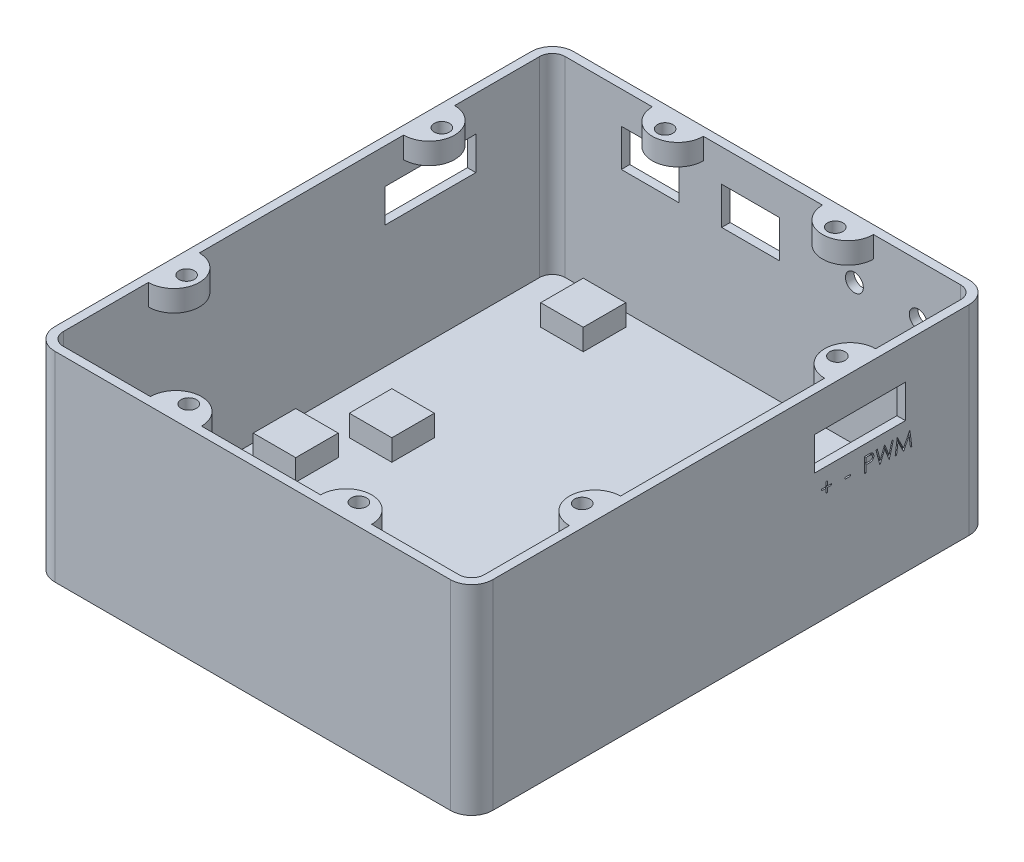
SolidWorks part; units mm, degrees
ref_plane "Alzado" through (0, 0, 0) normal (0, 0, 1) x (1, 0, 0)
ref_plane "Planta" through (0, 0, 0) normal (0, 1, 0) x (1, 0, 0)
ref_plane "Vista lateral" through (0, 0, 0) normal (1, 0, 0) x (0, 0, -1)
sketch "Croquis1" plane through (0, 0, 0) normal (0, 1, 0) x (1, 0, 0)
  line L0 (0, 0) -> (-10, 0) construction
  line L1 (0, 0) -> (93, 0) construction
  line L2 (0, 0) -> (0, 112) construction
  line L3 (0, 112) -> (93, 112) construction
  line L4 (93, 0) -> (93, 112) construction
  line L5 (0, 0) -> (0, -10) construction
  line L6 (0, -10) -> (-10, -10) construction
  line L7 (-10, -10) -> (-10, 0) construction
  line L8 (0, 0) -> (-3.5355, -3.5355) construction
  line L9 (-10, 0) -> (0, -10) construction
  line L10 (-5, -5) -> (-10, -10) construction
  line L15 (0, -5) -> (93, -5)
  line L16 (-5, 0) -> (-5, 112)
  line L17 (0, 117) -> (93, 117)
  line L18 (98, 0) -> (98, 112)
  arc A0 (-5, 0) -> (0, -5) centre (0, 0) ccw
  arc A1 (93, -5) -> (98, 0) centre (93, 0) ccw
  arc A2 (98, 112) -> (93, 117) centre (93, 112) ccw
  arc A3 (0, 117) -> (-5, 112) centre (0, 112) ccw
  point P10 (-5, -5)
  dimension "D5" = 5
  dimension "D1" = 112
  dimension "D2" = 93
extrude "Saliente-Extruir2" add sketch "Croquis1" along normal blind 47
shell "Vaciado3" thickness 2
sketch "Croquis2" plane through (0, 2, 0) normal (0, 1, 0) x (1, 0, 0)
  line L0 (46.5, -3) -> (46.5, 115) construction
  line L1 (0, -3) -> (93, -3) construction
  line L2 (93, 115) -> (0, 115) construction
  line L3 (96, 56) -> (-3, 56) construction
  line L4 (96, 0) -> (96, 112) construction
  line L5 (-3, 112) -> (-3, 0) construction
  line L6 (46.5, -3) -> (46.5, 0) construction
  line L7 (46.5, 115) -> (46.5, 112) construction
  line L8 (46.5, 0) -> (46.5, 51) construction
  line L9 (46.5, 115) -> (46.5, 60) construction
  line L10 (46.5, 112) -> (46.5, 57) construction
  line L11 (46.5, 112) -> (7.25, 112) construction
  line L12 (46.5, 112) -> (85.75, 112) construction
  line L13 (46.5, 0) -> (0, 0) construction
  line L14 (7.25, 57) -> (85.75, 57) construction
  line L15 (7.25, 57) -> (7.25, 112) construction
  line L16 (7.25, 112) -> (85.75, 112) construction
  line L17 (85.75, 57) -> (85.75, 112) construction
  line L18 (46.5, 0) -> (93, 0) construction
  line L20 (0, 0) -> (93, 0) construction
  line L21 (0, 0) -> (0, 51.6536) construction
  line L22 (0, 51.6536) -> (93, 51.6536) construction
  line L23 (93, 0) -> (93, 51.6536) construction
  line L24 (0, 0) -> (10, 0)
  line L25 (0, 0) -> (0, 10)
  line L26 (0, 10) -> (10, 10)
  line L27 (10, 0) -> (10, 10)
  line L28 (93, 0) -> (83, 0)
  line L29 (93, 0) -> (93, 10)
  line L30 (93, 10) -> (83, 10)
  line L31 (83, 0) -> (83, 10)
  line L32 (0, 51.6536) -> (10, 51.6536)
  line L33 (0, 51.6536) -> (0, 41.6536)
  line L34 (0, 41.6536) -> (10, 41.6536)
  line L35 (10, 51.6536) -> (10, 41.6536)
  line L36 (93, 51.6536) -> (83, 51.6536)
  line L37 (93, 51.6536) -> (93, 41.6536)
  line L38 (93, 41.6536) -> (83, 41.6536)
  line L39 (83, 51.6536) -> (83, 41.6536)
  line L40 (7.25, 57) -> (17.25, 57)
  line L41 (7.25, 57) -> (7.25, 67)
  line L42 (7.25, 67) -> (17.25, 67)
  line L43 (17.25, 57) -> (17.25, 67)
  line L44 (7.25, 112) -> (17.25, 112)
  line L45 (7.25, 112) -> (7.25, 102)
  line L46 (7.25, 102) -> (17.25, 102)
  line L47 (17.25, 112) -> (17.25, 102)
  line L48 (85.75, 57) -> (75.75, 57)
  line L49 (85.75, 57) -> (85.75, 67)
  line L50 (85.75, 67) -> (75.75, 67)
  line L51 (75.75, 57) -> (75.75, 67)
  line L52 (85.75, 112) -> (75.75, 112)
  line L53 (85.75, 112) -> (85.75, 102)
  line L54 (85.75, 102) -> (75.75, 102)
  line L55 (75.75, 112) -> (75.75, 102)
  dimension "D1" = 3
  dimension "D2" = 3
  dimension "D3" = 51
  dimension "D4" = 55
  dimension "D5" = 39.25
  dimension "D6" = 39.25
  dimension "D7" = 46.5
  dimension "D8" = 46.5
  dimension "D9" = 10
  dimension "D10" = 10
  dimension "D11" = 10
  dimension "D12" = 10
  dimension "D13" = 10
  dimension "D14" = 10
  dimension "D15" = 10
  dimension "D16" = 10
  dimension "D17" = 10
  dimension "D18" = 10
  dimension "D19" = 10
  dimension "D20" = 10
  dimension "D21" = 10
extrude "Saliente-Extruir3" add sketch "Croquis2" along normal blind 5
sketch "Croquis3" plane through (0, 47, 0) normal (0, 1, 0) x (1, 0, 0)
  line L0 (46.5, -3) -> (66.5, -3) construction
  line L1 (0, -3) -> (93, -3) construction
  line L2 (0, -3) -> (93, -3) construction
  line L3 (46.5, -3) -> (26.5, -3) construction
  line L4 (-3, 56) -> (-3, 86) construction
  line L5 (-3, 112) -> (-3, 0) construction
  line L6 (-3, 56) -> (-3, 26) construction
  line L7 (-3, 112) -> (-3, 0) construction
  line L8 (96, 56) -> (96, 86) construction
  line L9 (96, 0) -> (96, 112) construction
  line L10 (96, 56) -> (96, 26) construction
  line L11 (96, 0) -> (96, 112) construction
  line L12 (46.5, 115) -> (26.5, 115) construction
  line L13 (93, 115) -> (0, 115) construction
  line L14 (46.5, 115) -> (66.5, 115) construction
  line L15 (93, 115) -> (0, 115) construction
  line L16 (-3, 86) -> (3, 86) construction
  line L17 (-3, 26) -> (3, 26) construction
  line L18 (26.5, -3) -> (26.5, 3) construction
  line L19 (66.5, -3) -> (66.5, 3) construction
  line L20 (96, 26) -> (90, 26) construction
  line L21 (96, 86) -> (90, 86) construction
  line L22 (26.5, 115) -> (26.5, 109) construction
  line L23 (66.5, 115) -> (66.5, 109) construction
  line L24 (-3, 92) -> (-3, 80)
  line L25 (-3, 32) -> (-3, 20)
  line L26 (32.5, -3) -> (20.5, -3)
  line L27 (72.5, -3) -> (60.5, -3)
  line L28 (96, 32) -> (96, 20)
  line L29 (96, 92) -> (96, 80)
  line L30 (20.5, 115) -> (32.5, 115)
  line L31 (60.5, 115) -> (72.5, 115)
  circle A0 centre (-3, 86) radius 6 construction
  circle A1 centre (-3, 26) radius 6 construction
  circle A2 centre (96, 86) radius 6 construction
  circle A3 centre (96, 26) radius 6 construction
  circle A4 centre (26.5, 115) radius 6 construction
  circle A5 centre (66.5, 115) radius 6 construction
  circle A6 centre (26.5, -3) radius 6 construction
  circle A7 centre (66.5, -3) radius 6 construction
  arc A8 (20.5, 115) -> (32.5, 115) centre (26.5, 115) ccw
  arc A9 (72.5, 115) -> (60.5, 115) centre (66.5, 115) cw
  arc A10 (-3, 80) -> (-3, 92) centre (-3, 86) ccw
  arc A11 (-3, 20) -> (-3, 32) centre (-3, 26) ccw
  arc A12 (32.5, -3) -> (20.5, -3) centre (26.5, -3) ccw
  arc A13 (72.5, -3) -> (60.5, -3) centre (66.5, -3) ccw
  arc A14 (96, 32) -> (96, 20) centre (96, 26) ccw
  arc A15 (96, 92) -> (96, 80) centre (96, 86) ccw
  circle A16 centre (0, 86) radius 1.8
  circle A17 centre (26.5, 112) radius 1.8
  circle A18 centre (66.5, 112) radius 1.8
  circle A19 centre (93, 86) radius 1.8
  circle A20 centre (93, 26) radius 1.8
  circle A21 centre (66.5, 0) radius 1.8
  circle A22 centre (26.5, 0) radius 1.8
  circle A23 centre (0, 26) radius 1.8
  dimension "D9" = 12
  dimension "D10" = 12
  dimension "D11" = 12
  dimension "D12" = 12
  dimension "D13" = 12
  dimension "D14" = 12
  dimension "D15" = 12
  dimension "D16" = 12
  dimension "D17" = 3.6
  dimension "D18" = 3.6
  dimension "D19" = 3.6
  dimension "D20" = 3.6
  dimension "D21" = 3.6
  dimension "D22" = 3.6
  dimension "D23" = 3.6
  dimension "D24" = 3.6
  dimension "D1" = 20
  dimension "D2" = 20
  dimension "D3" = 20
  dimension "D4" = 20
  dimension "D5" = 30
  dimension "D6" = 30
  dimension "D7" = 30
  dimension "D8" = 30
extrude "Saliente-Extruir4" add sketch "Croquis3" against normal blind 5
sketch "Croquis4" plane through (-5, 0, 0) normal (-1, 0, 0) x (0, 0, 1)
  line L0 (-112, 47) -> (-112, 0) construction
  line L1 (-112, 47) -> (-112, 38.7) construction
  line L2 (-112, 38.7) -> (-97, 38.7) construction
  line L4 (-97, 38.7) -> (-75.66, 38.7)
  line L5 (-97, 38.7) -> (-97, 30.86)
  line L6 (-97, 30.86) -> (-75.66, 30.86)
  line L7 (-75.66, 38.7) -> (-75.66, 30.86)
  dimension "D1" = 8.3
  dimension "D2" = 15
  dimension "D3" = 21.34
  dimension "D4" = 7.84
extrude "Cortar-Extruir1" cut sketch "Croquis4" against normal blind 120
sketch "Croquis5" plane through (0, 0, -117) normal (0, 0, -1) x (-1, 0, 0)
  line L0 (-93, 47) -> (-93, 35) construction
  line L1 (-93, 47) -> (-93, 0) construction
  line L2 (-93, 35) -> (-83, 35) construction
  line L3 (0, 47) -> (0, 35) construction
  line L4 (0, 47) -> (0, 0) construction
  line L5 (0, 35) -> (-20, 35) construction
  line L6 (-20, 35) -> (-13.2, 35) construction
  line L7 (-13.2, 35) -> (-13.2, 39.4) construction
  line L9 (-13.2, 39.4) -> (-26.8, 39.4)
  line L10 (-13.2, 39.4) -> (-13.2, 30.6)
  line L11 (-13.2, 30.6) -> (-26.8, 30.6)
  line L12 (-26.8, 39.4) -> (-26.8, 30.6)
  circle A0 centre (-83, 35) radius 2.1
  dimension "D3" = 4.2
  dimension "D1" = 12
  dimension "D2" = 10
  dimension "D4" = 12
  dimension "D5" = 20
  dimension "D6" = 6.8
  dimension "D7" = 4.4
  dimension "D8" = 13.6
  dimension "D9" = 8.8
extrude "Cortar-Extruir2" cut sketch "Croquis5" against normal blind 2
sketch "Croquis6" plane through (-5, 0, 0) normal (-1, 0, 0) x (0, 0, 1)
  line L0 (-86.33, 30.86) -> (-86.33, 24.86) construction
  line L1 (-97, 30.86) -> (-75.66, 30.86) construction
  line L2 (-86.33, 24.86) -> (-75.66, 24.86) construction
  line L3 (-75.66, 24.86) -> (-97, 24.86) construction
  text T0 "<b>E1 E2 Ref</b>"
  dimension "D1" = 6
extrude "Cortar-Extruir3" cut sketch "Croquis6" against normal blind 0.4
sketch "Croquis7" plane through (98, 0, 0) normal (1, 0, 0) x (0, 0, -1)
  line L0 (86.33, 30.86) -> (86.33, 24.86) construction
  line L1 (97, 30.86) -> (75.66, 30.86) construction
  line L2 (86.33, 24.86) -> (75.66, 24.86) construction
  line L3 (75.66, 24.86) -> (97, 24.86) construction
  text T0 " +  -  PWM"
  dimension "D1" = 6
extrude "Cortar-Extruir4" cut sketch "Croquis7" against normal blind 0.4
sketch "Croquis8" plane through (0, 0, -117) normal (0, 0, -1) x (-1, 0, 0)
  line L0 (-26.8, 35) -> (-36.8, 35) construction
  line L1 (-26.8, 39.4) -> (-26.8, 30.6) construction
  line L2 (-36.8, 35) -> (-36.8, 39.4) construction
  line L3 (-83, 35) -> (-68, 35) construction
  line L4 (-36.8, 39.4) -> (-50.4, 39.4)
  line L5 (-36.8, 39.4) -> (-36.8, 30.6)
  line L6 (-36.8, 30.6) -> (-50.4, 30.6)
  line L7 (-50.4, 39.4) -> (-50.4, 30.6)
  circle A0 centre (-68, 35) radius 2.1
  dimension "D6" = 4.2
  dimension "D1" = 10
  dimension "D2" = 4.4
  dimension "D3" = 13.6
  dimension "D4" = 8.8
  dimension "D5" = 15
extrude "Cortar-Extruir5" cut sketch "Croquis8" against normal blind 2
sketch "Croquis9" plane through (0, 0, -117) normal (0, 0, -1) x (-1, 0, 0)
  line L0 (-43.6, 30.6) -> (-43.6, 24.6) construction
  line L1 (-50.4, 30.6) -> (-36.8, 30.6) construction
  line L2 (-43.6, 24.6) -> (-50.4, 24.6) construction
  line L3 (-50.4, 24.6) -> (-13.2, 24.6) construction
  line L4 (-83, 35) -> (-83, 24.6) construction
  line L5 (-87.7584, 24.6) -> (-64.3027, 24.6) construction
  text T0 "<b>Motor      Emg</b>" font "Century Gothic" height in points 10
  text T1 "<b>Motor               Emg</b>" font "Century Gothic" height in points 10
  dimension "D1" = 6
  dimension "D2" = 10.4
extrude "Cortar-Extruir6" cut sketch "Croquis9" against normal blind 0.4
